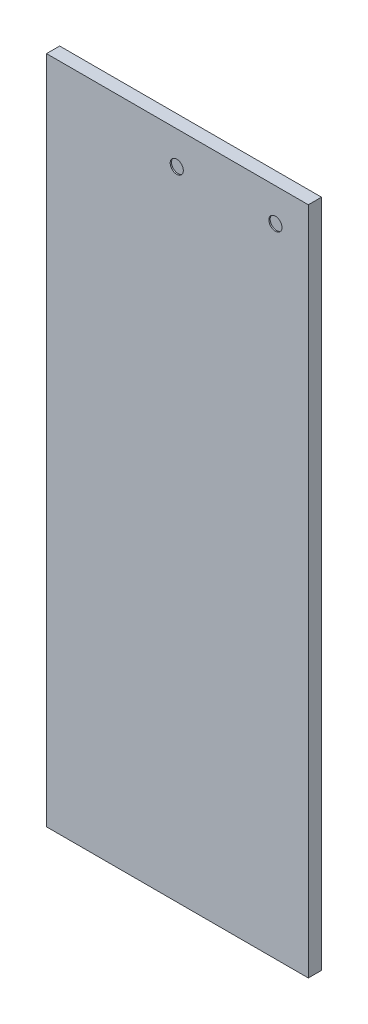
SolidWorks part; units mm, degrees
ref_plane "Front Plane" through (0, 0, 0) normal (0, 0, 1) x (1, 0, 0)
ref_plane "Top Plane" through (0, 0, 0) normal (0, 1, 0) x (1, 0, 0)
ref_plane "Right Plane" through (0, 0, 0) normal (1, 0, 0) x (0, 0, -1)
sketch "Sketch1" plane through (0, 0, 0) normal (0, 0, 1) x (1, 0, 0)
  line L1 (199, -509) -> (-199, -509)
  line L2 (199, -509) -> (199, 509)
  line L3 (199, 509) -> (-199, 509)
  line L4 (-199, -509) -> (-199, 509)
  line L5 (199, -509) -> (-199, 509) construction
  line L6 (199, 509) -> (-199, -509) construction
  point P0 (0, 0)
  dimension "D1" = 1018
  dimension "D2" = 398
extrude "Boss-Extrude1" add sketch "Sketch1" along normal blind 20
sketch "Sketch2" plane through (0, 0, 20) normal (0, 0, 1) x (1, 0, 0)
  line L0 (149, 509) -> (149, -509) construction
  line L1 (199, 509) -> (-199, 509) construction
  line L2 (-199, -509) -> (199, -509) construction
  line L3 (-199, 459) -> (199, 459) construction
  line L4 (-199, 509) -> (-199, -509) construction
  line L5 (199, -509) -> (199, 509) construction
  line L6 (149, 459) -> (-1, 459) construction
  circle A0 centre (149, 459) radius 10
  circle A1 centre (-1, 459) radius 10
  dimension "D3" = 150
  dimension "D1" = 50
  dimension "D2" = 50
extrude "Cut-Extrude1" cut sketch "Sketch2" against normal blind 2
